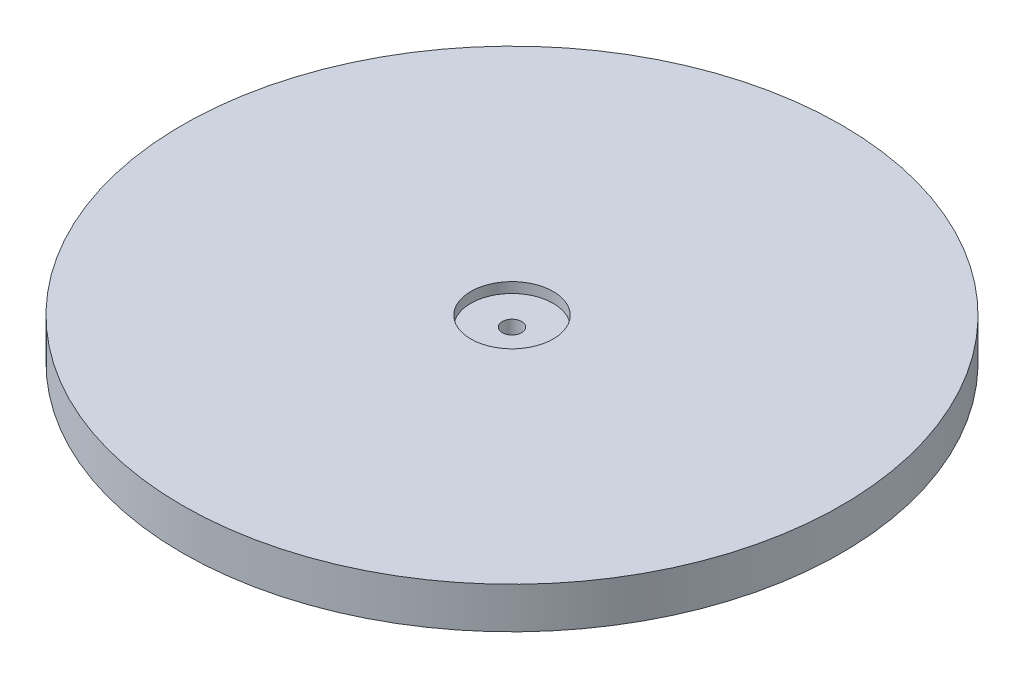
SolidWorks part; units mm, degrees
ref_plane "Front Plane" through (0, 0, 0) normal (0, 0, 1) x (1, 0, 0)
ref_plane "Top Plane" through (0, 0, 0) normal (0, 1, 0) x (1, 0, 0)
ref_plane "Right Plane" through (0, 0, 0) normal (1, 0, 0) x (0, 0, -1)
sketch "Sketch1" plane through (0, 0, 0) normal (0, 1, 0) x (1, 0, 0)
  circle A0 centre (0, 0) radius 101.6
  circle A1 centre (0, 0) radius 3
  dimension "D1" = 203.2
  dimension "D2" = 6
extrude "Boss-Extrude1" add sketch "Sketch1" along normal blind 12.7
sketch "Sketch5" plane through (0, 12.7, 0) normal (0, 1, 0) x (1, 0, 0)
  circle A1 centre (0, 0) radius 101.6
  circle A2 centre (0, 0) radius 101.6
  dimension "D1" = 0
sketch "Sketch7" plane through (0, 12.7, 0) normal (0, 1, 0) x (1, 0, 0)
  circle A0 centre (0, 0) radius 3 construction
  circle A1 centre (0, 0) radius 101.6 construction
  circle A2 centre (0, 0) radius 3
  circle A3 centre (0, 0) radius 101.6
extrude "Boss-Extrude3" add sketch "Sketch7" along normal blind 6.35
sketch "Sketch8" plane through (0, 19.05, 0) normal (0, 1, 0) x (1, 0, 0)
  circle A0 centre (0, 0) radius 12.7
  dimension "D1" = 25.4
extrude "Cut-Extrude1" cut sketch "Sketch8" against normal blind 6.35
sketch "Sketch9" plane through (0, 0, 0) normal (0, -1, 0) x (1, 0, 0)
  circle A0 centre (0, 0) radius 12.7
  dimension "D1" = 25.4
extrude "Cut-Extrude2" cut sketch "Sketch9" against normal blind 6.35
sketch "Sketch10" plane through (0, 0, 0) normal (0, -1, 0) x (1, 0, 0)
  circle A1 centre (0, 0) radius 101.6
  circle A2 centre (0, 0) radius 101.6
  dimension "D1" = 0
extrude "Cut-Extrude3" cut sketch "Sketch10" against normal blind 6.35
sketch "Sketch11" plane through (0, 6.35, 0) normal (0, -1, 0) x (1, 0, 0)
  circle A0 centre (0, 0) radius 25
  dimension "D1" = 50
sketch "Sketch12" plane through (0, 12.7, 0) normal (0, 1, 0) x (1, 0, 0)
  circle A1 centre (0, 0) radius 12.7
  circle A2 centre (0, 0) radius 12.7
  dimension "D1" = 0
extrude "Boss-Extrude4" add sketch "Sketch12" along normal blind 3.175
sketch "Sketch13" plane through (0, 12.7, 0) normal (0, -1, 0) x (1, 0, 0)
  circle A0 centre (0, 0) radius 3 construction
  circle A1 centre (0, 0) radius 3
extrude "Cut-Extrude6" cut sketch "Sketch13" against normal blind 3.175
